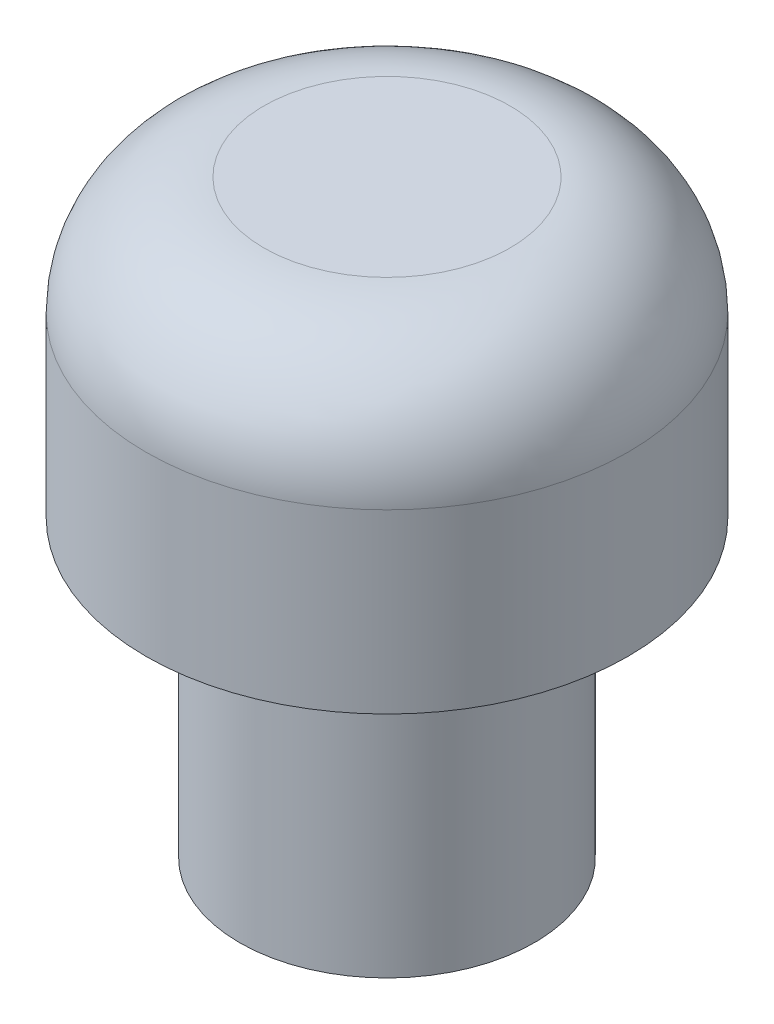
SolidWorks part; units mm, degrees
ref_plane "Front Plane" through (0, 0, 0) normal (0, 0, 1) x (1, 0, 0)
ref_plane "Top Plane" through (0, 0, 0) normal (0, 1, 0) x (1, 0, 0)
ref_plane "Right Plane" through (0, 0, 0) normal (1, 0, 0) x (0, 0, -1)
sketch "Sketch1" plane through (0, 0, 0) normal (0, 1, 0) x (1, 0, 0)
  circle A0 centre (0, 0) radius 3.175
  dimension "D1" = 6.35
extrude "Boss-Extrude1" add sketch "Sketch1" along normal blind 6.35
sketch "Sketch2" plane through (0, 6.35, 0) normal (0, 1, 0) x (1, 0, 0)
  circle A0 centre (0, 0) radius 5.192
extrude "Boss-Extrude2" add sketch "Sketch2" along normal blind 6.35
fillet "Fillet1" radius 2.54 1 edges at (0, 12.7, 5.192)
